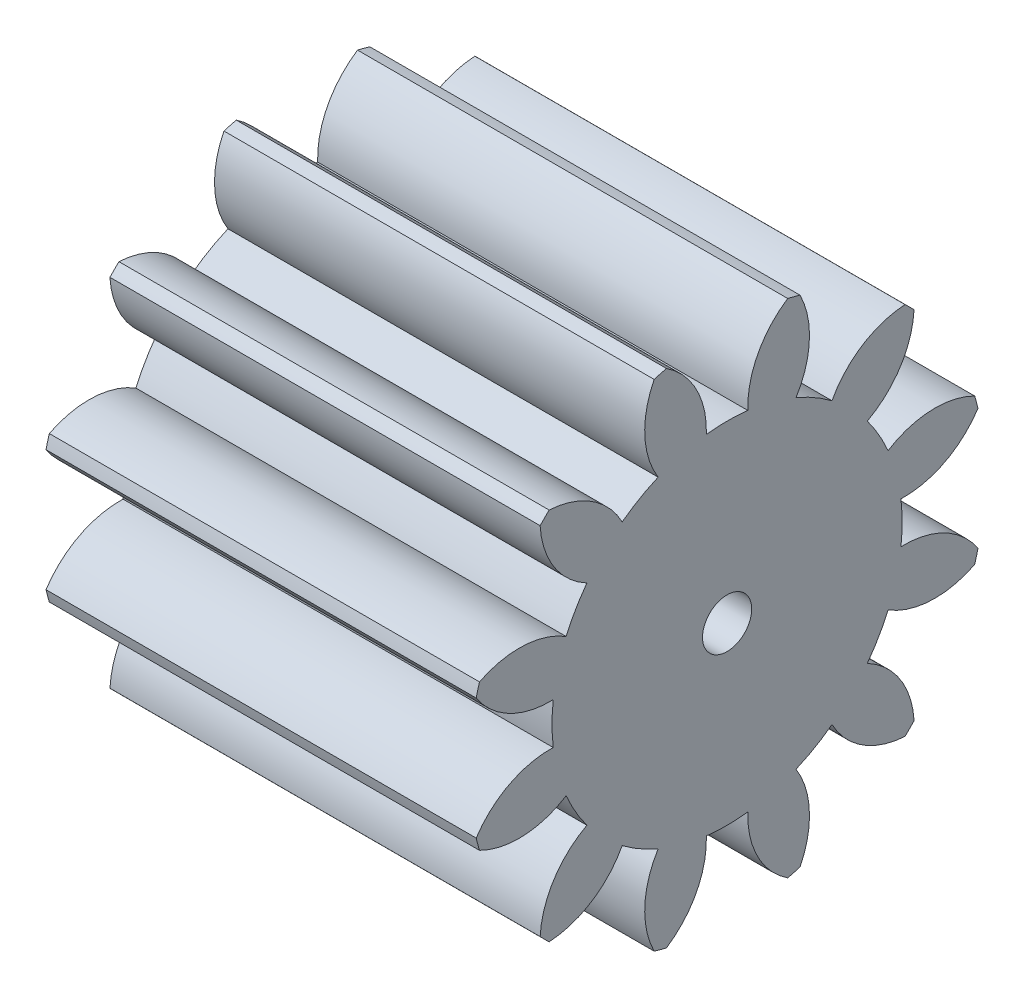
SolidWorks part; units mm, degrees
ref_plane "Plane1" through (0, 0, 0) normal (0, 0, 1) x (1, 0, 0)
ref_plane "Plane2" through (0, 0, 0) normal (0, 1, 0) x (1, 0, 0)
ref_plane "Plane3" through (0, 0, 0) normal (1, 0, 0) x (0, 0, -1)
other "Configuration Table"
sketch "HoldingSke" plane through (0, 0, 0) normal (0, 1, 0) x (1, 0, 0)
  line L0 (0, 0) -> (1.6302, -0.3465)
  line L1 (-15, 0) -> (100, 0) construction
  line L2 (0, 0) -> (-2.1039, 2.3779)
  line L3 (0, 0) -> (-11.863, 4.5341)
  line L4 (0, 0) -> (8.4473, 1.7955)
  line L5 (0, 0) -> (-46.8476, -17.4728)
  line L6 (0, 0) -> (-5.8027, -3.9151)
  line L7 (-2.1039, 2.3779) -> (8.6586, 51.2059)
  line L8 (-76.2, 54.61) -> (-76.1, 54.61)
  line L9 (-71.009, 38.7566) -> (-53.1078, 45.2721)
  line L10 (-76.2, 71.12) -> (104.1128, 71.12)
  line L11 (0, 0) -> (-7, 0)
  line L12 (-76.2, 101.6) -> (-76.177, 101.6)
  line L13 (24.9733, 27.94) -> (52.9518, 28.4284)
  line L14 (24.9733, 27.94) -> (24.9743, 27.94)
  line L15 (24.9733, 27.94) -> (100.4006, 29.5858)
  line L16 (-63.627, -0.6) -> (-12.827, -0.6)
  circle A0 centre (0, 0) radius 0.4
  circle A1 centre (0, 0) radius 2.849
  circle A2 centre (0, 0) radius 37.5
  circle A3 centre (0, 0) radius 0.4
  dimension "MHD" = 5.698
  dimension "Hub_dia" = 75
  dimension "Bore" = 0.8
  dimension "MBD" = 0.8
  dimension "Num_teeth" = 12
  dimension "Pitch" = 1.6667
  dimension "Overall_len" = 50
  dimension "Show_teeth" = 12
  dimension "Thickness" = 7
  dimension "OAL" = 50.0001
  dimension "T_dim" = 0.1
  dimension "Ap" = 20
  dimension "H" = 19.05
  dimension "Pitch_radius" = 180.3128
  dimension "Width" = 7
  dimension "Backlash" = 0.023
  dimension "Addendum_fac" = 1
  dimension "Dedendum_fac" = 1.25
  dimension "Clearance_fac" = 0.25
  dimension "Dedendum_add" = 0.001
  dimension "Module" = 0.6
sketch "BasProSke" plane through (0, 0, 0) normal (0, 1, 0) x (1, 0, 0)
  line L0 (-10, 0) -> (60, 0) construction
  line L1 (0, 0) -> (0, 4.2)
  line L2 (0, 0) -> (7, 0)
  line L3 (7, 0) -> (7, 4.2)
  line L4 (7, 4.2) -> (0, 4.2)
  dimension "Thickness" = 7
  dimension "Diameter" = 8.4
revolve "Base-Revolve" add sketch "BasProSke" angle 360 about L0
sketch "TooCutSke" plane through (0, 0, 0) normal (1, 0, 0) x (0, 0, -1)
  line L1 (0, 0) -> (0, 107) construction
  line L2 (0, 0) -> (-0.5101, 3.5637) construction
  line L3 (0, 0) -> (-1.8502, 6.905) construction
  line L4 (-0.5101, 3.5637) -> (-0.9251, 3.4525) construction
  arc A0 (0.3376, 2.8289) -> (-0.3376, 2.8289) centre (0, 0) ccw
  arc A1 (1.0161, 4.1014) -> (-1.0161, 4.1014) centre (0, 0) ccw
  circle A2 centre (0, 0) radius 3.6 construction
  circle A3 centre (0, 0) radius 3.3829 construction
  arc A4 (-0.3376, 2.8289) -> (-1.0161, 4.1014) centre (-1.7768, 2.8787) ccw
  arc A5 (1.0161, 4.1014) -> (0.3376, 2.8289) centre (1.7768, 2.8787) ccw
  dimension "Root_dia" = 5.698
  dimension "Overcut_dia" = 8.4508
  dimension "Pitch_dia" = 7.2
  dimension "Base_dia" = 6.7658
  dimension "Flank_rad" = 1.44
  dimension "Half_ang" = 15
  dimension "Half_CT" = 0.4296
extrude "ToothCut" cut sketch "TooCutSke" along normal through all
fillet "Breaks" [suppressed] radius 0.012
fillet "RootFillets" [suppressed] radius 0.151
pattern_circular "TeethCuts" count 12 every 30 about axis through (-10, 0, 0) along (1, 0, 0) of "ToothCut", "RootFillets", "Breaks"
sketch "HubNeaOneSke" plane through (0, 0, 0) normal (-1, 0, 0) x (0, 0, 1)
  circle A0 centre (0, 0) radius 2.849
  dimension "Diameter" = 5.698
extrude "HubNearOne" [suppressed] add sketch "HubNeaOneSke" along normal blind 43.0001
sketch "HubNeaBotSke" plane through (0, 0, 0) normal (-1, 0, 0) x (0, 0, 1)
  circle A0 centre (0, 0) radius 2.849
  dimension "Diameter" = 5.698
extrude "HubNearBoth" [suppressed] add sketch "HubNeaBotSke" along normal blind 21.5
ref_plane "FarPln" through (7, 0, 0) normal (1, 0, 0) x (0, 0, -1)
sketch "HubFarSke" plane through (7, 0, 0) normal (1, 0, 0) x (0, 0, -1)
  circle A0 centre (0, 0) radius 2.849
  dimension "Diameter" = 5.698
extrude "HubFar" [suppressed] add sketch "HubFarSke" along normal blind 21.5
sketch "BorSke" plane through (0, 0, 0) normal (1, 0, 0) x (0, 0, -1)
  circle A0 centre (0, 0) radius 0.4
  dimension "Diameter" = 0.8
extrude "Bore" cut sketch "BorSke" along normal mid plane 100.0001
sketch "KeySke" plane through (0, 0, 0) normal (1, 0, 0) x (0, 0, -1)
  line L0 (-0.05, 0) -> (-0.05, 0.5)
  line L1 (-0.05, 0.5) -> (0.05, 0.5)
  line L2 (0.05, 0.5) -> (0.05, 0)
  line L3 (0, 0) -> (0, 34) construction
  line L4 (-0.05, 0) -> (0.05, 0)
  dimension "Offset" = 0.5
  dimension "Width" = 0.1
extrude "Keyway" [suppressed] cut sketch "KeySke" along normal mid plane 100.0001
pattern_circular "Keyway2" [suppressed] count 2 every 90 about axis through (-10, 0, 0) along (1, 0, 0)
equation "' \"Module@HoldingSke\" = 6.35"
equation "' \"Num_teeth@HoldingSke\" = 12"
equation "' \"Ap@HoldingSke\" =  20"
equation "' \"Ap@HoldingSke\" = 20"
equation "' \"Width@HoldingSke\" = 0.5 * 25.4"
equation "' \"Hub_dia@HoldingSke\"= 1 * 25.4"
equation "' \"Hub_dia@HoldingSke\" = 1 * 25.4"
equation "' \"Overall_len@HoldingSke\" = 1.0 * 25.4"
equation "' \"Bore@HoldingSke\" = 0.75 * 25.4"
equation "' \"T_dim@HoldingSke\" = 0.1 * 25.4"
equation "' \"Width@KeySke\" = 0.25 * 25.4"
equation "' \"Show_teeth@HoldingSke\" = 13"
equation "' \"Backlash@HoldingSke\" = 0.009 * 25.4"
equation "' \"Addendum_fac@HoldingSke\" = 1.0"
equation "' \"Dedendum_fac@HoldingSke\" = 1.25"
equation "' \"Dedendum_add@HoldingSke\" = 0.00005 * 25.4"
equation "' \"Clearance_fac@HoldingSke\" = 0.25"
equation "\"Pitch@HoldingSke\" = 1 / \"Module@HoldingSke\""
equation "\"Overcut_dia@TooCutSke\" = (\"Num_teeth@HoldingSke\" + 2 * \"Addendum_fac@HoldingSke\") / \"Pitch@HoldingSke\" + 0.002 * 25.4"
equation "\"Pitch_dia@TooCutSke\" = \"Num_teeth@HoldingSke\" / \"Pitch@HoldingSke\""
equation "\"Base_dia@TooCutSke\" = \"Num_teeth@HoldingSke\" / \"Pitch@HoldingSke\" * cos((\"Ap@HoldingSke\"  * 3.14159265 / 180))"
equation "\"Root_dia@TooCutSke\" = (\"Num_teeth@HoldingSke\" + 2) / \"Pitch@HoldingSke\" - 2 * (\"Addendum_fac@HoldingSke\" + \"Dedendum_fac@HoldingSke\") / \"Pitch@HoldingSke\" - \"Dedendum_add@HoldingSke\" * 2"
equation "\"Half_ang@TooCutSke\" = 180 / \"Num_teeth@HoldingSke\""
equation "\"Half_CT@TooCutSke\" = \"Num_teeth@HoldingSke\" / \"Pitch@HoldingSke\" * sin((3.14159265 / 2 / \"Num_teeth@HoldingSke\")) / 2 - 7 * \"Backlash@HoldingSke\" / 4"
equation "\"Flank_rad@TooCutSke\" = \"Num_teeth@HoldingSke\" / \"Pitch@HoldingSke\" / 5"
equation "\"Radius@RootFillets\" = \"Clearance_fac@HoldingSke\" / \"Pitch@HoldingSke\" + \"Dedendum_add@HoldingSke\""
equation "\"Break_rad@Breaks\" = 0.02 / \"Pitch@HoldingSke\""
equation "\"Thickness@HoldingSke\" = \"Width@HoldingSke\""
equation "\"OAL@HoldingSke\" = \"Thickness@HoldingSke\""
equation "\"MHD@HoldingSke\" = (\"Num_teeth@HoldingSke\" + 2) / \"Pitch@HoldingSke\" - 2 * (\"Addendum_fac@HoldingSke\" + \"Dedendum_fac@HoldingSke\")  / \"Pitch@HoldingSke\" - \"Dedendum_add@HoldingSke\" * 2"
equation "\"MBD@HoldingSke\" = (\"Num_teeth@HoldingSke\" + 2) / \"Pitch@HoldingSke\" - 2 * (\"Addendum_fac@HoldingSke\" + \"Dedendum_fac@HoldingSke\")  / \"Pitch@HoldingSke\" - \"Dedendum_add@HoldingSke\" * 2 - 0.002 * 25.4"
equation "\"MHD@HoldingSke\" = ((sgn( \"MHD@HoldingSke\" - \"Hub_dia@HoldingSke\" )-1)*( \"MHD@HoldingSke\" - \"Hub_dia@HoldingSke\" ))/-2+ \"Hub_dia@HoldingSke\""
equation "\"MBD@HoldingSke\" = ((sgn( \"MBD@HoldingSke\" - \"Bore@HoldingSke\" )-1)*( \"MBD@HoldingSke\" - \"Bore@HoldingSke\" ))/-2+ \"Bore@HoldingSke\""
equation "\"OAL@HoldingSke\" = ((sgn( \"OAL@HoldingSke\" - \"Overall_len@HoldingSke\" )+1)*( \"OAL@HoldingSke\" - \"Overall_len@HoldingSke\" ))/2 + \"Overall_len@HoldingSke\" + 0.000002 * 25.4"
equation "\"Num_teeth@TeethCuts\" = int( \"Show_teeth@HoldingSke\" ) + 1"
equation "\"Num_teeth@TeethCuts\" = ((sgn( \"Num_teeth@TeethCuts\" - \"Num_teeth@HoldingSke\" )-1)*( \"Num_teeth@TeethCuts\" - \"Num_teeth@HoldingSke\" ))/-2+ \"Num_teeth@HoldingSke\""
equation "\"Num_teeth@TeethCuts\" = ((sgn( \"Num_teeth@TeethCuts\" - 2.0)+1)*( \"Num_teeth@TeethCuts\" - 2.0))/2 +2.0"
equation "\"Angle@TeethCuts\" = 360.0 / \"Num_teeth@HoldingSke\""
equation "\"Diameter@BasProSke\" = (\"Num_teeth@HoldingSke\" + 2 * \"Addendum_fac@HoldingSke\") / \"Pitch@HoldingSke\""
equation "\"Thickness@BasProSke\"  = \"Thickness@HoldingSke\""
equation "' \"Fillet_rad@BasProSke\" =  \"Thickness@HoldingSke\" * 0.05"
equation "' \"Fillet_rad@BasProSke\" = \"Thickness@HoldingSke\" * 0.05"
equation "\"MHD@HoldingSke\" = ((sgn( \"MHD@HoldingSke\" - \"Root_dia@TooCutSke\" )-1)*( \"MHD@HoldingSke\" - \"Root_dia@TooCutSke\" ))/-2+ \"Root_dia@TooCutSke\""
equation "\"Diameter@HubNeaOneSke\" = \"MHD@HoldingSke\""
equation "\"Length@HubNearOne\" = \"OAL@HoldingSke\" - \"Thickness@BasProSke\""
equation "\"Diameter@HubNeaBotSke\" = \"MHD@HoldingSke\""
equation "\"Length@HubNearBoth\" = ( \"OAL@HoldingSke\" - \"Thickness@BasProSke\" ) / 2.0"
equation "\"Thickness@FarPln\" = \"Thickness@BasProSke\""
equation "\"Diameter@HubFarSke\" = \"MHD@HoldingSke\""
equation "\"Length@HubFar\" = ( \"OAL@HoldingSke\" - \"Thickness@BasProSke\" ) / 2.0"
equation "\"Diameter@BorSke\" = \"MBD@HoldingSke\""
equation "\"D1@Bore\" = \"OAL@HoldingSke\" * 2.0"
equation "\"D1@Keyway\" = \"OAL@HoldingSke\" * 2.0"
equation "\"Offset@KeySke\" = \"T_dim@HoldingSke\" + \"MBD@HoldingSke\" / 2.0"
